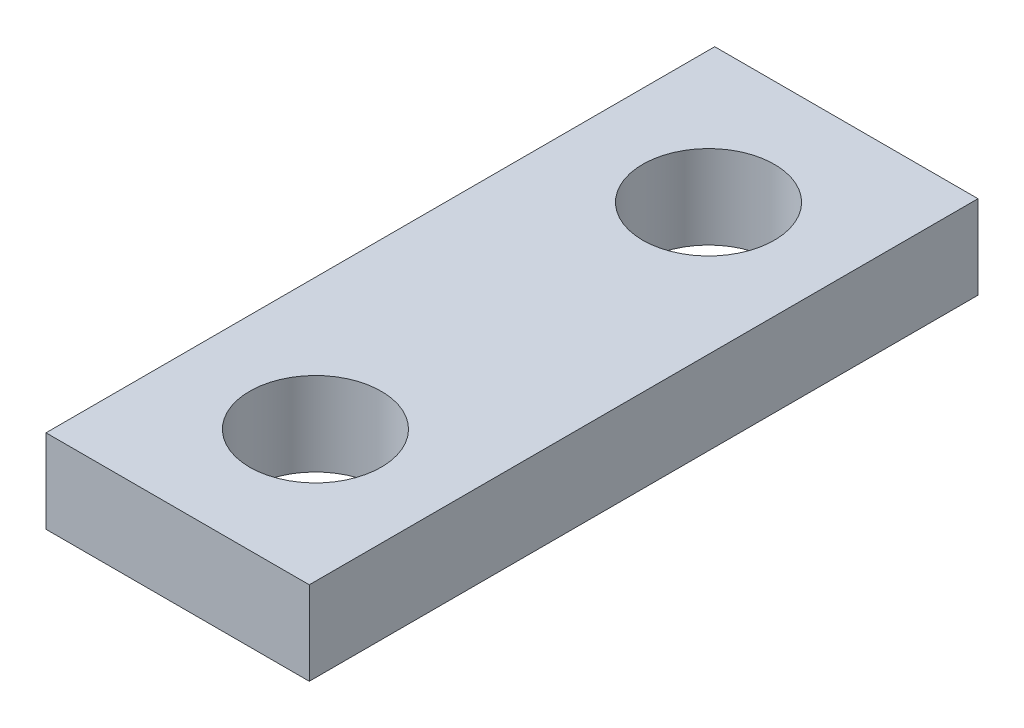
SolidWorks part; units mm, degrees
ref_plane "Front Plane" through (0, 0, 0) normal (0, 0, 1) x (1, 0, 0)
ref_plane "Top Plane" through (0, 0, 0) normal (0, 1, 0) x (1, 0, 0)
ref_plane "Right Plane" through (0, 0, 0) normal (1, 0, 0) x (0, 0, -1)
sketch "Sketch1" plane through (0, 0, 0) normal (0, 1, 0) x (1, 0, 0)
  line L1 (-5, -12.7) -> (5, -12.7)
  line L2 (-5, -12.7) -> (-5, 12.7)
  line L3 (-5, 12.7) -> (5, 12.7)
  line L4 (5, -12.7) -> (5, 12.7)
  line L5 (-5, -12.7) -> (5, 12.7) construction
  line L6 (-5, 12.7) -> (5, -12.7) construction
  point P0 (0, 0)
  dimension "D1" = 10
  dimension "D2" = 25.4
extrude "Boss-Extrude1" add sketch "Sketch1" along normal mid plane 3.175
sketch "Sketch2" plane through (0, 1.5875, 0) normal (0, 1, 0) x (1, 0, 0)
  line L0 (0, 0) -> (50000, 0) construction
  circle A0 centre (0, 7.465) radius 2.5
  circle A1 centre (0, -7.465) radius 2.5
  point P2 (0, 0)
  dimension "D2" = 5
  dimension "D1" = 14.93
extrude "Cut-Extrude1" cut sketch "Sketch2" against normal through all
